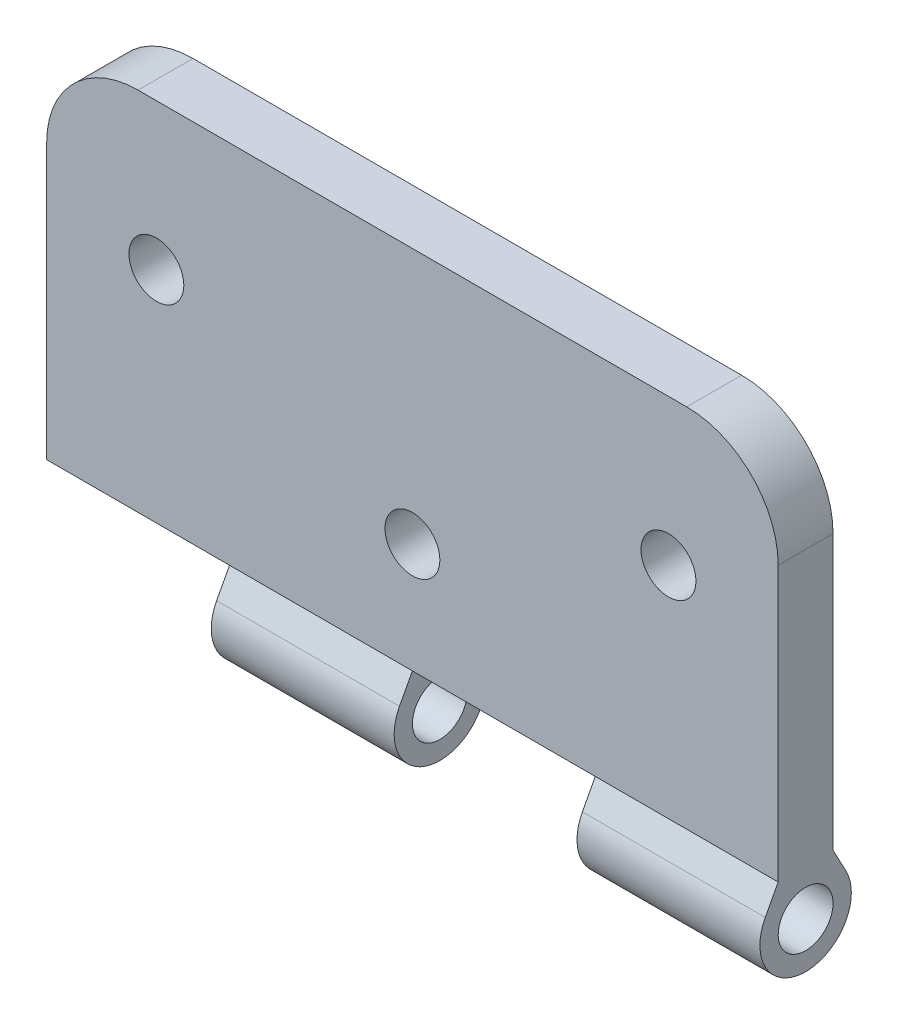
SolidWorks part; units mm, degrees
ref_plane "Plan de face" through (0, 0, 0) normal (0, 0, 1) x (1, 0, 0)
ref_plane "Plan de dessus" through (0, 0, 0) normal (0, 1, 0) x (1, 0, 0)
ref_plane "Plan de droite" through (0, 0, 0) normal (1, 0, 0) x (0, 0, -1)
sketch "Esquisse1" plane through (0, 0, 0) normal (0, 0, 1) x (1, 0, 0)
  line L1 (-15, 10) -> (15, 10)
  line L2 (-20, 5) -> (-20, -10)
  line L3 (-20, -10) -> (20, -10)
  line L4 (20, 5) -> (20, -10)
  line L5 (-20, 10) -> (20, -10) construction
  line L6 (-20, -10) -> (20, 10) construction
  arc A0 (15, 10) -> (20, 5) centre (15, 5) cw
  arc A1 (-15, 10) -> (-20, 5) centre (-15, 5) ccw
  point P0 (0, 0)
  dimension "D3" = 5
  dimension "D1" = 40
  dimension "D2" = 20
extrude "Boss.-Extru.1" add sketch "Esquisse1" along normal blind 3
sketch "Esquisse2" plane through (20, 0, 0) normal (1, 0, 0) x (0, 0, -1)
  line L0 (-1.5, -13.8713) -> (-1.5, 5.2546) construction
  line L3 (-3, -10) -> (-3.7059, -11.3235)
  line L4 (0, -10) -> (0.7059, -11.3235)
  line L5 (-3, -10) -> (0, -10) construction
  line L6 (-3, -10) -> (0, -10)
  arc A0 (-3.7059, -11.3235) -> (0.7059, -11.3235) centre (-1.5, -12.5) ccw
  circle A1 centre (-1.5, -12.5) radius 1.5
  point P6 (-0.0886, -12.0279)
  point P8 (-1.718, -12.3929)
  dimension "D1" = 5
  dimension "D3" = 3
extrude "Boss.-Extru.2" add sketch "Esquisse2" against normal blind 10
pattern_linear "Répétition linéaire1" count 2 spacing 20 along (-1, 0, 0) of "Boss.-Extru.2"
sketch "Esquisse3" plane through (0, 0, 3) normal (0, 0, 1) x (1, 0, 0)
  line L0 (0, -10) -> (10, -10) construction
  line L1 (-20, -10) -> (-10, -10) construction
  line L2 (0, 18.3284) -> (0, -26.4322) construction
  line L3 (-20, 5) -> (-20, -10) construction
  circle A0 centre (0, -4) radius 1.5
  circle A1 centre (-14, 2) radius 1.5
  circle A2 centre (14, 2) radius 1.5
  dimension "D1" = 3
  dimension "D3" = 3
  dimension "D2" = 6
  dimension "D4" = 12
  dimension "D5" = 6
extrude "Enlèv. mat.-Extru.1" cut sketch "Esquisse3" against normal blind 10
